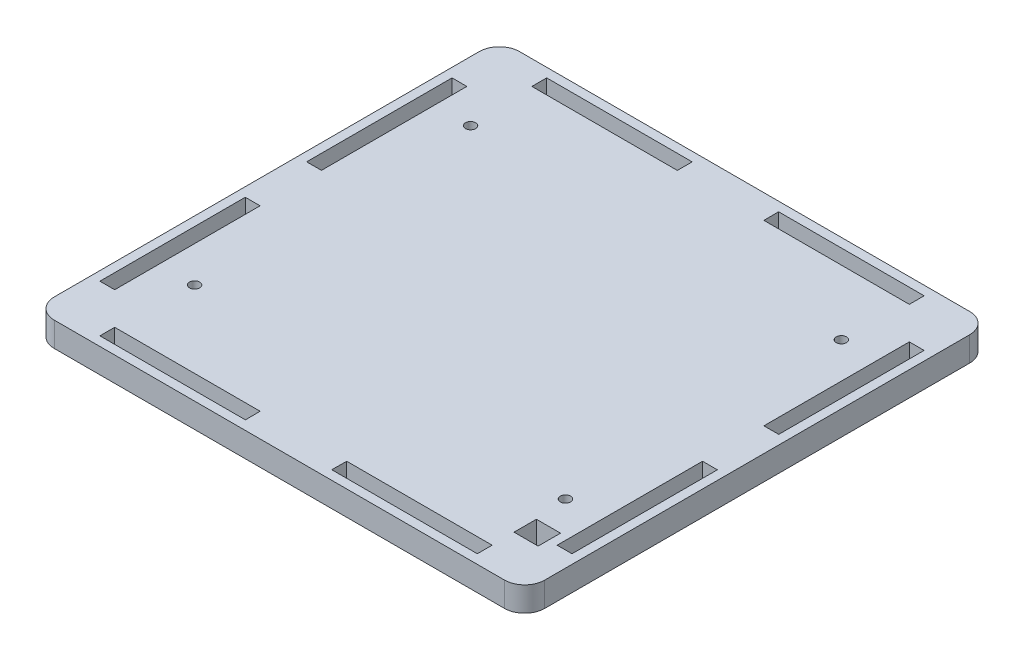
SolidWorks part; units mm, degrees
ref_plane "Front Plane" through (0, 0, 0) normal (0, 0, 1) x (1, 0, 0)
ref_plane "Top Plane" through (0, 0, 0) normal (0, 1, 0) x (1, 0, 0)
ref_plane "Right Plane" through (0, 0, 0) normal (1, 0, 0) x (0, 0, -1)
sketch "Sketch1" plane through (0, 0, 0) normal (0, 1, 0) x (1, 0, 0)
  line L0 (-1000, 0) -> (49000, 0) construction
  line L1 (-54.229, 51.435) -> (54.229, 51.435)
  line L2 (-54.229, 51.435) -> (-54.229, -51.435)
  line L3 (-54.229, -51.435) -> (54.229, -51.435)
  line L4 (54.229, 51.435) -> (54.229, -51.435)
  line L5 (0, -1000) -> (0, 49000) construction
  line L6 (-51.943, 38.6842) -> (-49.1744, 38.6842) construction
  line L7 (-51.943, -38.6842) -> (-49.1744, -38.6842) construction
  line L8 (-51.943, -38.6842) -> (-51.943, -7.0358) construction
  line L9 (-51.943, -7.0358) -> (-49.1744, -7.0358) construction
  line L10 (-49.1744, -38.6842) -> (-49.1744, -7.0358) construction
  line L11 (-49.1744, 38.6842) -> (-49.1744, 7.0358) construction
  line L12 (-51.943, 7.0358) -> (-49.1744, 7.0358) construction
  line L13 (-51.943, 38.6842) -> (-51.943, 7.0358) construction
  line L14 (51.943, -38.6842) -> (49.1744, -38.6842) construction
  line L15 (51.943, -38.6842) -> (51.943, -7.0358) construction
  line L16 (49.1744, -38.6842) -> (49.1744, -7.0358) construction
  line L17 (51.943, -7.0358) -> (49.1744, -7.0358) construction
  line L18 (51.943, 7.0358) -> (49.1744, 7.0358) construction
  line L19 (51.943, 38.6842) -> (51.943, 7.0358) construction
  line L20 (51.943, 38.6842) -> (49.1744, 38.6842) construction
  line L21 (49.1744, 38.6842) -> (49.1744, 7.0358) construction
  line L22 (41.4782, -46.3804) -> (9.8298, -46.3805) construction
  line L23 (41.4782, -49.149) -> (9.8044, -49.149) construction
  line L24 (9.8298, -46.3805) -> (9.8044, -49.149) construction
  line L25 (41.4782, -46.3804) -> (41.4782, -49.149) construction
  line L26 (-41.4782, -46.3804) -> (-41.4782, -49.149) construction
  line L27 (-41.4782, -49.149) -> (-9.8044, -49.149) construction
  line L28 (-9.8298, -46.3805) -> (-9.8044, -49.149) construction
  line L29 (-41.4782, -46.3804) -> (-9.8298, -46.3805) construction
  line L30 (41.4782, 46.3804) -> (41.4782, 49.149) construction
  line L31 (41.4782, 49.149) -> (9.8044, 49.149) construction
  line L32 (41.4782, 46.3804) -> (9.8298, 46.3805) construction
  line L33 (9.8298, 46.3805) -> (9.8044, 49.149) construction
  line L34 (-9.8298, 46.3805) -> (-9.8044, 49.149) construction
  line L35 (-41.4782, 49.149) -> (-9.8044, 49.149) construction
  line L36 (-41.4782, 46.3804) -> (-41.4782, 49.149) construction
  line L37 (-41.4782, 46.3804) -> (-9.8298, 46.3805) construction
  line L38 (41.7322, 46.1264) -> (41.7322, 49.403)
  line L39 (41.7322, 49.403) -> (9.5481, 49.403)
  line L40 (9.5781, 46.1265) -> (9.5481, 49.403)
  line L41 (41.7322, 46.1264) -> (9.5781, 46.1265)
  line L42 (-9.5781, 46.1265) -> (-9.5481, 49.403)
  line L43 (-41.7322, 49.403) -> (-9.5481, 49.403)
  line L44 (-41.7322, 46.1264) -> (-41.7322, 49.403)
  line L45 (-41.7322, 46.1264) -> (-9.5781, 46.1265)
  line L46 (52.197, -38.9382) -> (48.9204, -38.9382)
  line L47 (48.9204, -38.9382) -> (48.9204, -6.7818)
  line L48 (52.197, -6.7818) -> (48.9204, -6.7818)
  line L49 (52.197, -38.9382) -> (52.197, -6.7818)
  line L50 (52.197, 6.7818) -> (48.9204, 6.7818)
  line L51 (48.9204, 38.9382) -> (48.9204, 6.7818)
  line L52 (52.197, 38.9382) -> (48.9204, 38.9382)
  line L53 (52.197, 38.9382) -> (52.197, 6.7818)
  line L54 (41.7322, -46.1264) -> (9.5781, -46.1265)
  line L55 (9.5781, -46.1265) -> (9.5481, -49.403)
  line L56 (41.7322, -49.403) -> (9.5481, -49.403)
  line L57 (41.7322, -46.1264) -> (41.7322, -49.403)
  line L58 (-41.7322, -46.1264) -> (-41.7322, -49.403)
  line L59 (-41.7322, -49.403) -> (-9.5481, -49.403)
  line L60 (-9.5781, -46.1265) -> (-9.5481, -49.403)
  line L61 (-41.7322, -46.1264) -> (-9.5781, -46.1265)
  line L62 (-52.197, 38.9382) -> (-48.9204, 38.9382)
  line L63 (-48.9204, 38.9382) -> (-48.9204, 6.7818)
  line L64 (-52.197, 6.7818) -> (-48.9204, 6.7818)
  line L65 (-52.197, 38.9382) -> (-52.197, 6.7818)
  line L66 (-52.197, -38.9382) -> (-48.9204, -38.9382)
  line L67 (-48.9204, -38.9382) -> (-48.9204, -6.7818)
  line L68 (-52.197, -6.7818) -> (-48.9204, -6.7818)
  line L69 (-52.197, -38.9382) -> (-52.197, -6.7818)
  circle A0 centre (-40.9956, -29.1846) radius 1.1303
  circle A1 centre (40.9956, -29.1846) radius 1.1303
  circle A2 centre (-40.9956, 31.8262) radius 1.1303
  circle A3 centre (40.9956, 31.8262) radius 1.1303
  dimension "D5" = 2.2606
  dimension "D8" = 2.2606
  dimension "D1" = 108.458
  dimension "D2" = 102.87
  dimension "D3" = 54.229
  dimension "D4" = 51.435
  dimension "D6" = 13.2334
  dimension "D7" = 22.2504
  dimension "D9" = 13.2334
  dimension "D10" = 19.6088
  dimension "D11" = 12.7508
  dimension "D12" = 31.6484
  dimension "D13" = 2.7686
  dimension "D14" = 2.286
  dimension "D15" = 2.286
  dimension "D16" = 12.7508
  dimension "D17" = 31.6484
  dimension "D18" = 2.7686
  dimension "D19" = 0.254
  dimension "D20" = 0.254
  dimension "D21" = 0.254
  dimension "D22" = 0.254
extrude "Boss-Extrude1" add sketch "Sketch1" along normal mid plane 5.4356
fillet "Fillet1" radius 4.445 4 edges at (-54.229, 0, -51.435) (-54.229, 0, 51.435) (54.229, 0, 51.435) (54.229, 0, -51.435)
sketch "Sketch3" plane through (0, 2.7178, 0) normal (0, 1, 0) x (1, 0, 0)
  line L0 (44.323, -36.2585) -> (44.323, -41.2115) construction
  line L1 (41.656, -36.2585) -> (46.99, -36.2585)
  line L2 (41.656, -36.2585) -> (41.656, -41.2115)
  line L3 (41.656, -41.2115) -> (46.99, -41.2115)
  line L4 (46.99, -36.2585) -> (46.99, -41.2115)
  line L5 (-49.784, -51.435) -> (49.784, -51.435) construction
  line L6 (41.656, -38.735) -> (46.99, -38.735) construction
  line L8 (54.229, -46.99) -> (54.229, 46.99) construction
  point P7 (44.323, -38.735)
  dimension "D1" = 5.334
  dimension "D2" = 4.953
  dimension "D3" = 12.7
  dimension "D5" = 9.906
extrude "Cut-Extrude2" cut sketch "Sketch3" against normal through all
equation "\"D3@Sketch1\"=.5*\"D1@Sketch1\""
equation "\"D4@Sketch1\"=.5*\"D2@Sketch1\""
